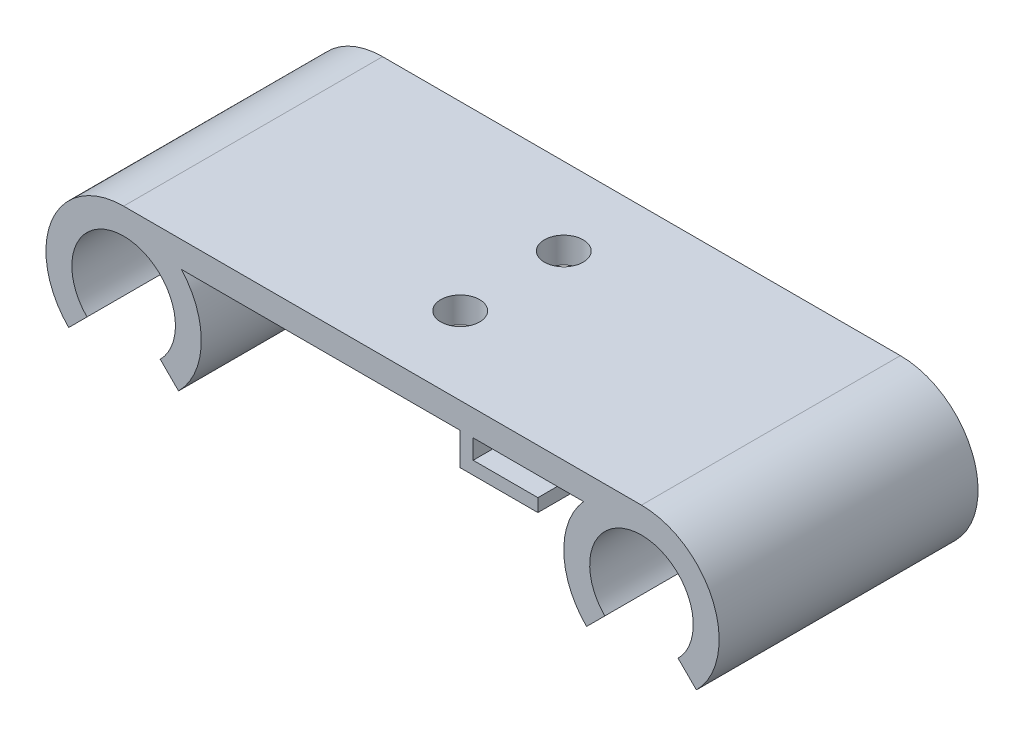
SolidWorks part; units mm, degrees
ref_plane "Plan de face" through (0, 0, 0) normal (0, 0, 1) x (1, 0, 0)
ref_plane "Plan de dessus" through (0, 0, 0) normal (0, 1, 0) x (1, 0, 0)
ref_plane "Plan de droite" through (0, 0, 0) normal (1, 0, 0) x (0, 0, -1)
sketch "Esquisse1" plane through (0, 0, 0) normal (0, 0, 1) x (1, 0, 0)
  line L0 (10.4721, 10) -> (41.5279, 10)
  line L1 (46, 0) -> (47.1992, 0)
  line L2 (0, 0) -> (0, 12)
  line L3 (0, 12) -> (52, 12)
  line L4 (52, 0) -> (52, 12)
  line L5 (32, 10) -> (32, 7.5)
  line L6 (32, 7.5) -> (38, 7.5)
  line L7 (38, 7.5) -> (38, 8.5)
  line L8 (38, 8.5) -> (33, 8.5)
  line L9 (33, 8.5) -> (33, 10)
  line L10 (6, 6) -> (0, 0)
  line L11 (6, 6) -> (12, 0)
  line L12 (46, 6) -> (50.2426, 1.7574)
  line L13 (46, 6) -> (41.7574, 1.7574)
  circle A0 centre (6, 6) radius 4
  circle A1 centre (6, 6) radius 6
  circle A2 centre (46, 6) radius 6
  circle A3 centre (46, 6) radius 4
  arc A4 (41.5279, 2) -> (50.2426, 1.7574) centre (46, 6) ccw
  dimension "D3" = 12
  dimension "D4" = 8
  dimension "D5" = 12
  dimension "D6" = 8
  dimension "D1" = 12
  dimension "D2" = 52
  dimension "D7" = 6
  dimension "D8" = 6
  dimension "D9" = 6
  dimension "D10" = 6
  dimension "D11" = 1
  dimension "D12" = 1
  dimension "D13" = 1.5
  dimension "D14" = 6
  dimension "D15" = 20
  dimension "D16" = 90
extrude "Boss.-Extru.1" add sketch "Esquisse1" along normal blind 20 contours A1 L10 A0 L11 | A2 L3 A1 L0 | A3 L12 A2 L13 | L8 L9 L0 L5 L6 L7
sketch "Esquisse2" plane through (0, 12, 0) normal (0, 1, 0) x (1, 0, 0)
  line L0 (6, 0) -> (46, 0) construction
  line L1 (6, -20) -> (46, -20) construction
  line L2 (46, -20) -> (46, 0) construction
  line L3 (6, -20) -> (6, 0) construction
  circle A0 centre (26, -6) radius 1.5
  circle A1 centre (26, -14) radius 1.5
  dimension "D1" = 3
  dimension "D2" = 3
  dimension "D3" = 6
  dimension "D4" = 6
  dimension "D5" = 20
  dimension "D6" = 20
extrude "Enlèv. mat.-Extru.1" cut sketch "Esquisse2" against normal blind 20
